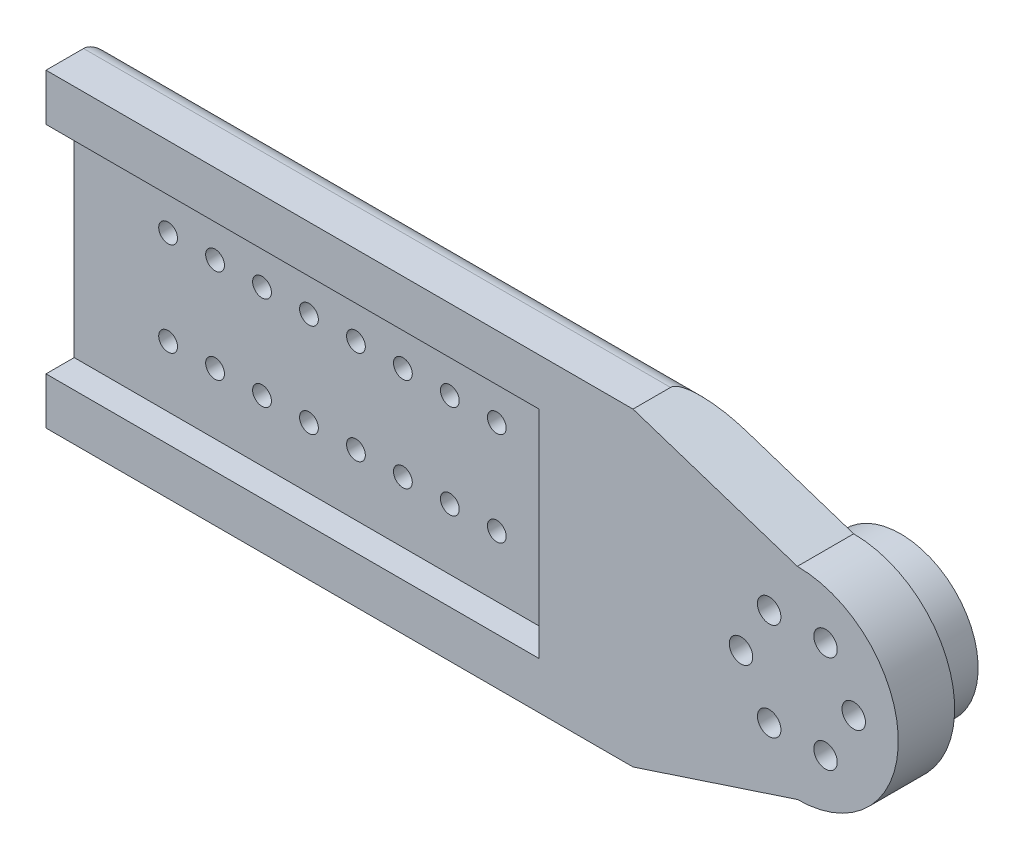
SolidWorks part; units mm, degrees
ref_plane "前视基准面" through (0, 0, 0) normal (0, 0, 1) x (1, 0, 0)
ref_plane "上视基准面" through (0, 0, 0) normal (0, 1, 0) x (1, 0, 0)
ref_plane "右视基准面" through (0, 0, 0) normal (1, 0, 0) x (0, 0, -1)
sketch "草图1" plane through (0, 0, 0) normal (0, 0, 1) x (1, 0, 0)
  line L0 (0, 0) -> (-45, 0) construction
  line L4 (45, -21.5) -> (45, 21.5) construction
  line L5 (-45, -21.5) -> (45, 21.5) construction
  line L6 (-45, 21.5) -> (45, -21.5) construction
  line L7 (10, -33) -> (-45, -33)
  line L10 (10, 33) -> (-45, 33)
  line L17 (10, 33) -> (45, 21.5)
  line L18 (10, -33) -> (45, -21.5)
  line L19 (-45, 33) -> (-45, -33) construction
  line L20 (-45, 33) -> (-115, 33)
  line L21 (-115, 33) -> (-115, -33)
  line L22 (-115, -33) -> (-45, -33)
  arc A0 (45, 21.5) -> (45, -21.5) centre (45, 0) cw
  circle A1 centre (-35, 10) radius 2
  circle A2 centre (-25, 10) radius 2
  circle A3 centre (-25, -10) radius 2
  circle A4 centre (-35, -10) radius 2
  circle A5 centre (-55, 10) radius 2
  circle A6 centre (-55, -10) radius 2
  circle A7 centre (-45, -10) radius 2
  circle A8 centre (-45, 10) radius 2
  circle A9 centre (-75, 10) radius 2
  circle A10 centre (-75, -10) radius 2
  circle A11 centre (-65, -10) radius 2
  circle A12 centre (-65, 10) radius 2
  circle A13 centre (-95, 10) radius 2
  circle A14 centre (-95, -10) radius 2
  circle A15 centre (-85, -10) radius 2
  circle A16 centre (-85, 10) radius 2
  point P0 (0, 0)
  dimension "D6" = 4
  dimension "D8" = 20
  dimension "D9" = 10
  dimension "D10" = 45
  dimension "D12" = 70
  dimension "D1" = 43
  dimension "D2" = 90
  dimension "D3" = 55
  dimension "D7" = 66
  dimension "D11" = 35
  dimension "D13" = 70
  dimension "D4" = 2
  dimension "D5" = 2
  dimension "D14" = 4
extrude "凸台-拉伸1" add sketch "草图1" along normal blind 12
sketch "草图6" plane through (0, 0, 0) normal (0, 0, -1) x (-1, 0, 0)
  line L0 (-45, 21.5) -> (-45, -21.5) construction
  circle A0 centre (-45, 0) radius 16.5
  point P10 (-45, 0)
  dimension "D1" = 33
extrude "凸台-拉伸3" add sketch "草图6" along normal blind 10
sketch "草图7" plane through (0, 0, -10) normal (0, 0, -1) x (-1, 0, 0)
  line L1 (-33, 0) -> (-39, 10.3923) construction
  line L2 (-39, 10.3923) -> (-51, 10.3923) construction
  line L3 (-51, 10.3923) -> (-57, 0) construction
  line L4 (-57, 0) -> (-51, -10.3923) construction
  line L5 (-51, -10.3923) -> (-39, -10.3923) construction
  line L6 (-39, -10.3923) -> (-33, 0) construction
  circle A0 centre (-45, 0) radius 12 construction
  circle A1 centre (-51, 10.3923) radius 2.5
  circle A2 centre (-39, 10.3923) radius 2.5
  circle A3 centre (-33, 0) radius 2.5
  circle A4 centre (-39, -10.3923) radius 2.5
  circle A5 centre (-51, -10.3923) radius 2.5
  circle A6 centre (-57, 0) radius 2.5
  point P23 (-45, 0)
  dimension "D1" = 5
  dimension "D2" = 6
extrude "切除-拉伸3" cut sketch "草图7" against normal through all
sketch "草图10" plane through (0, 0, 12) normal (0, 0, 1) x (1, 0, 0)
  line L0 (0, 0) -> (-115, 0) construction
  line L1 (-115, 33) -> (-115, -33) construction
  line L2 (-115, -23) -> (-115, 23)
  line L3 (-115, 23) -> (-10, 23)
  line L4 (-10, 23) -> (-10, -23)
  line L5 (10, 33) -> (-115, 33) construction
  line L6 (-115, -23) -> (-10, -23)
  point P11 (-10, 0)
  dimension "D1" = 10
  dimension "D2" = 10
extrude "切除-拉伸5" cut sketch "草图10" against normal blind 6
fillet "圆角1" radius 4 3 edges at (-115, 0, 0) (-52.5, 33, 0) (-52.5, -33, 0)
